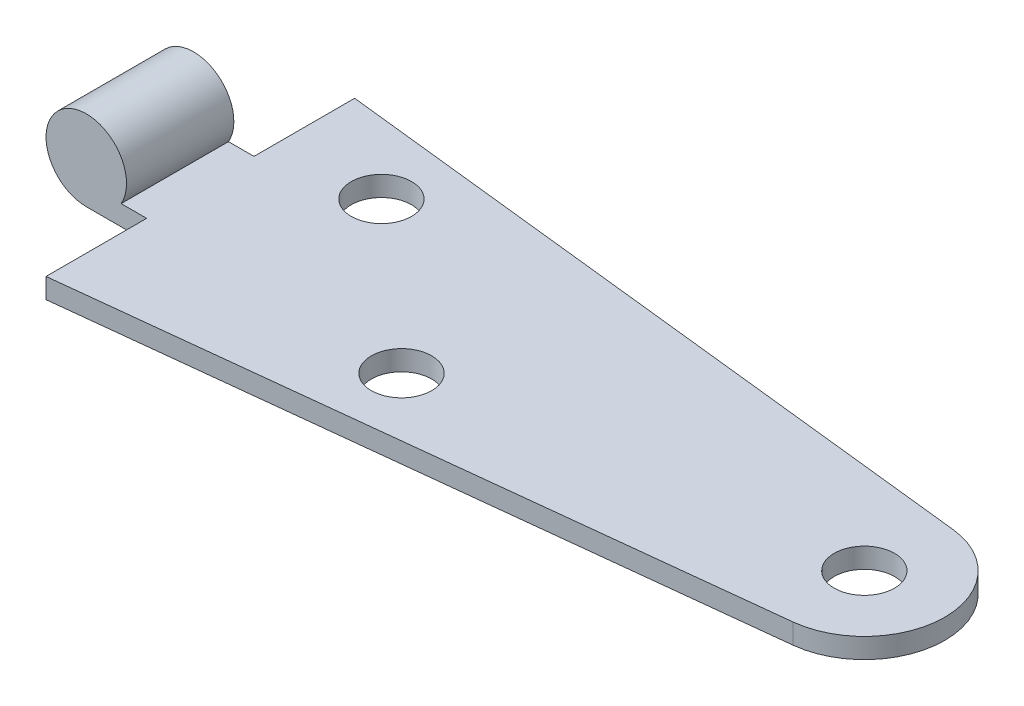
SolidWorks part; units mm, degrees
ref_plane "Front Plane" through (0, 0, 0) normal (0, 0, 1) x (1, 0, 0)
ref_plane "Top Plane" through (0, 0, 0) normal (0, 1, 0) x (1, 0, 0)
ref_plane "Right Plane" through (0, 0, 0) normal (1, 0, 0) x (0, 0, -1)
sketch "Sketch1" plane through (0, 0, 0) normal (0, 1, 0) x (1, 0, 0)
  line L0 (-57.15, 12.7) -> (-57.15, -12.7)
  line L1 (-57.15, 12.7) -> (0.697, 6.3116)
  line L2 (-57.15, -12.7) -> (0.697, -6.3116)
  arc A0 (0.697, -6.3116) -> (0.697, 6.3116) centre (0, 0) ccw
  circle A1 centre (0, 0) radius 2.3813
  circle A2 centre (-44.45, 6.35) radius 2.3812
  circle A3 centre (-31.75, -4.7625) radius 2.3812
  point P5 (-6.35, 0)
  point P6 (-57.15, 0)
  dimension "D1" = 25.4
  dimension "D3" = 12.7
  dimension "D4" = 4.7625
  dimension "D5" = 6.35
  dimension "D6" = 4.7625
  dimension "D8" = 4.7625
  dimension "D2" = 50.8
  dimension "D7" = 12.7
  dimension "D9" = 25.4
  dimension "D10" = 7.9375
extrude "Boss-Extrude1" add sketch "Sketch1" along normal blind 1.5875
sketch "Sketch2" plane through (-57.15, 0, 0) normal (-1, 0, 0) x (0, 0, 1)
  line L0 (-12.7, 3.175) -> (12.7, 3.175) construction
  line L1 (-12.7, 0) -> (12.7, 0) construction
  line L3 (-12.7, 3.175) -> (12.7, 3.175)
  line L4 (-12.7, 3.175) -> (-12.7, 0)
  line L5 (-12.7, 0) -> (12.7, 0)
  line L6 (12.7, 3.175) -> (12.7, 0)
  dimension "D1" = 3.175
revolve "Revolve1" add sketch "Sketch2" angle 360 about L0
sketch "Sketch3" plane through (0, 1.5875, 0) normal (0, 1, 0) x (1, 0, 0)
  line L0 (-60.325, 12.7) -> (-60.325, -12.7) construction
  line L1 (-52.3875, 4.2333) -> (-60.325, 4.2333)
  line L3 (-52.3875, -4.2333) -> (-60.325, -4.2333)
  line L4 (-52.3875, -4.2333) -> (-52.3875, -12.7)
  line L5 (-53.975, 12.7) -> (-60.325, 12.7) construction
  line L6 (-60.325, -4.2333) -> (-60.325, -12.7)
  line L7 (-60.325, 12.7) -> (-52.3875, 12.7)
  line L8 (-60.325, 12.7) -> (-60.325, 4.2333)
  line L9 (-60.325, -12.7) -> (-52.3875, -12.7)
  line L10 (-52.3875, 12.7) -> (-52.3875, 4.2333)
  dimension "D1" = 8.4667
  dimension "D2" = 8.4667
  dimension "D4" = 7.9375
  dimension "D5" = 25.4
extrude "Cut-Extrude1" cut sketch "Sketch3" against normal through all and the other way through all
